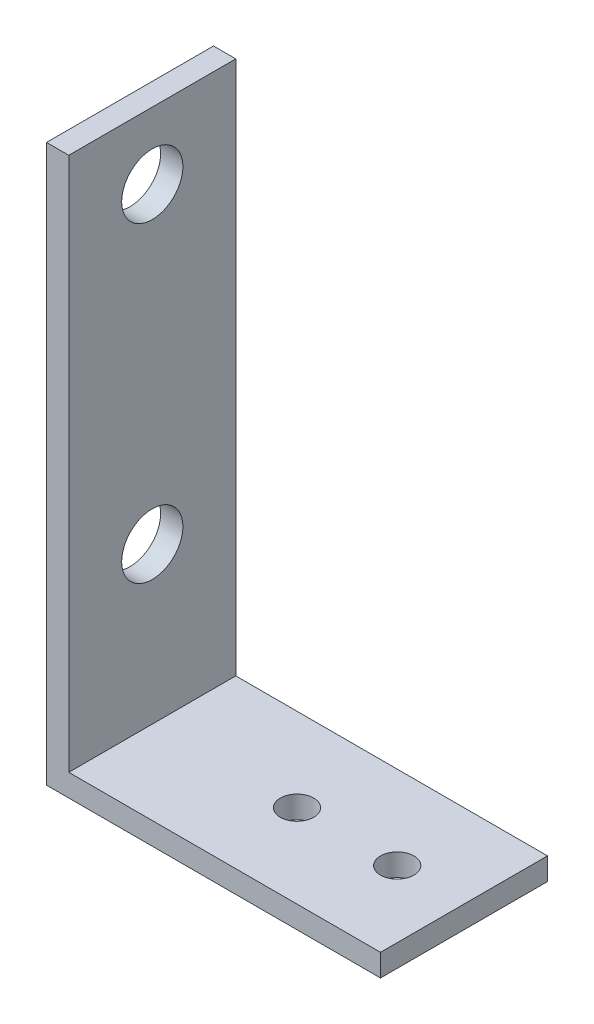
SolidWorks part; units mm, degrees
ref_plane "Piano frontale" through (0, 0, 0) normal (0, 0, 1) x (1, 0, 0)
ref_plane "Piano superiore" through (0, 0, 0) normal (0, 1, 0) x (1, 0, 0)
ref_plane "Piano destro" through (0, 0, 0) normal (1, 0, 0) x (0, 0, -1)
sketch "Schizzo1" plane through (0, 0, 0) normal (0, 0, 1) x (1, 0, 0)
  line L0 (0, 0) -> (-30, 0)
  line L1 (-30, 0) -> (-30, 50)
  line L2 (-30, 50) -> (-28, 50)
  line L3 (-28, 50) -> (-28, 2)
  line L4 (-28, 2) -> (0, 2)
  line L5 (0, 2) -> (0, 0)
  dimension "D1" = 50
  dimension "D2" = 2
  dimension "D3" = 30
  dimension "D4" = 2
extrude "Estrusione-Estrusione1" add sketch "Schizzo1" along normal blind 15
sketch "Schizzo2" plane through (-30, 0, 0) normal (-1, 0, 0) x (0, 0, 1)
  line L0 (7.5, 50) -> (7.5, 0) construction
  line L1 (15, 50) -> (0, 50) construction
  line L2 (15, 0) -> (0, 0) construction
  circle A0 centre (7.5, 44) radius 2.75
  circle A1 centre (7.5, 16) radius 2.75
  dimension "D2" = 5.5
  dimension "D3" = 5.5
  dimension "D1" = 28
  dimension "D4" = 6
extrude "Taglio-Estrusione1" cut sketch "Schizzo2" against normal blind 15
sketch "Schizzo3" plane through (0, 0, 0) normal (0, -1, 0) x (1, 0, 0)
  line L0 (0, 7.5) -> (-30, 7.5) construction
  line L1 (0, 15) -> (0, 0) construction
  line L2 (-30, 15) -> (-30, 0) construction
  circle A0 centre (-6, 7.5) radius 1.5
  circle A1 centre (-15, 7.5) radius 1.5
  point P12 (-6.0966, 12.732)
  dimension "D1" = 3
  dimension "D2" = 3
  dimension "D3" = 9
  dimension "D4" = 6
extrude "Taglio-Estrusione2" cut sketch "Schizzo3" against normal blind 15
